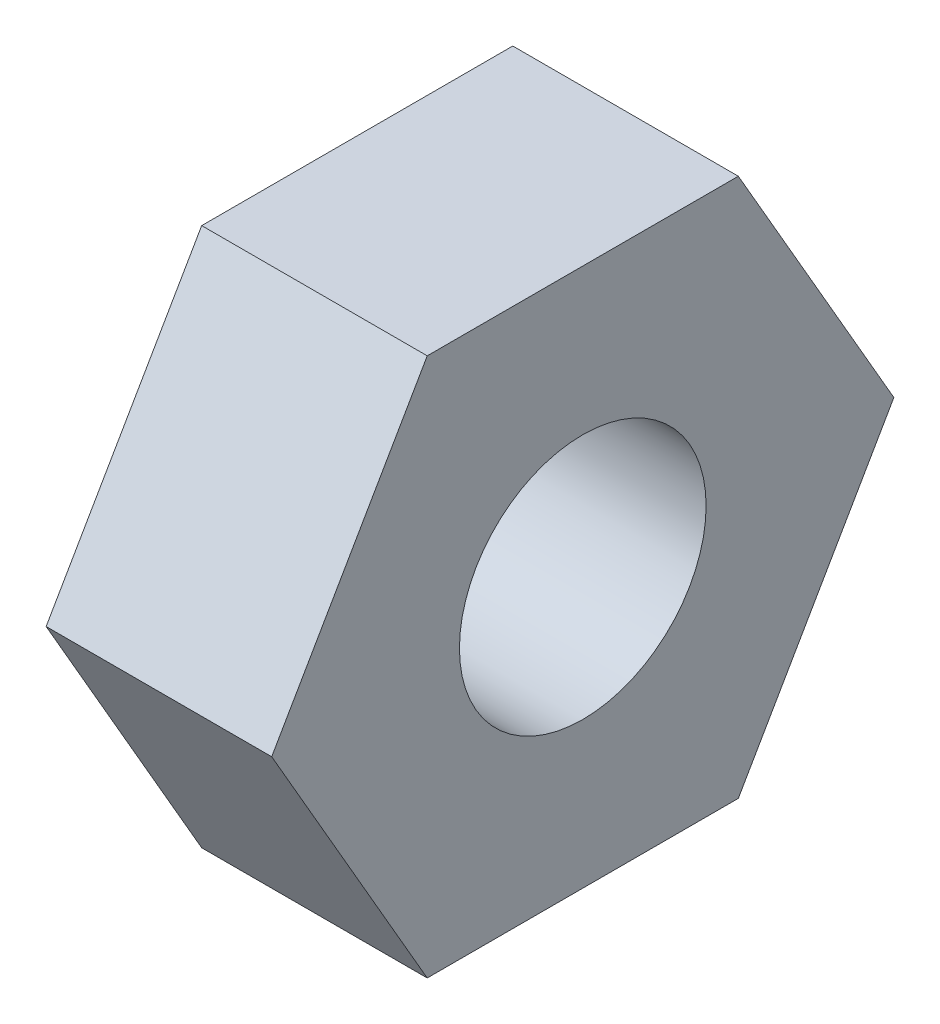
SolidWorks part; units mm, degrees
material "ASTM A36 Steel"
ref_plane "Front Plane" through (0, 0, 0) normal (1, 0, 0) x (0, 1, 0)
ref_plane "Top Plane" through (0, 0, 0) normal (0, 0, 1) x (0, 1, 0)
ref_plane "Right Plane" through (0, 0, 0) normal (0, 1, 0) x (-1, 0, 0)
sketch "Sketch1" plane through (0, 0, 0) normal (1, 0, 0) x (0, 1, 0)
  line L1 (0, -3.1529) -> (2.7305, -1.5765)
  line L2 (2.7305, -1.5765) -> (2.7305, 1.5765)
  line L3 (2.7305, 1.5765) -> (0, 3.1529)
  line L4 (0, 3.1529) -> (-2.7305, 1.5765)
  line L5 (-2.7305, 1.5765) -> (-2.7305, -1.5765)
  line L6 (-2.7305, -1.5765) -> (0, -3.1529)
  circle A0 centre (0, 0) radius 2.7305 construction
  dimension "D1" = 5.461
extrude "Boss-Extrude1" add sketch "Sketch1" along normal blind 2.286
hole_wizard "Tap Drill for M3x0.5 Tap1" positions "Sketch2" profile "Sketch3" hole size "M3x0.5" standard "ANSI Metric"
sketch "Sketch2" plane through (2.286, 0, 0) normal (1, 0, 0) x (0, 0, -1)
  point P0 (0, 0)
sketch "Sketch3" plane through (2.286, 0, 0) normal (0, 1, 0) x (0, 0, -1)
  line L0 (0, 0) -> (0, 26.1511)
  line L1 (0, 26.1511) -> (1.25, 25.4)
  line L2 (1.25, 25.4) -> (1.25, 0)
  line L5 (1.25, 0) -> (0, 0)
  line L10 (0, 26.1511) -> (-1.25, 25.4) construction
  line L11 (0, -6.35) -> (0, 107.95) construction
  dimension "Hole Dia." = 2.5
  dimension "Hole Depth" = 25.4
  dimension "Drill Angle" = 118
